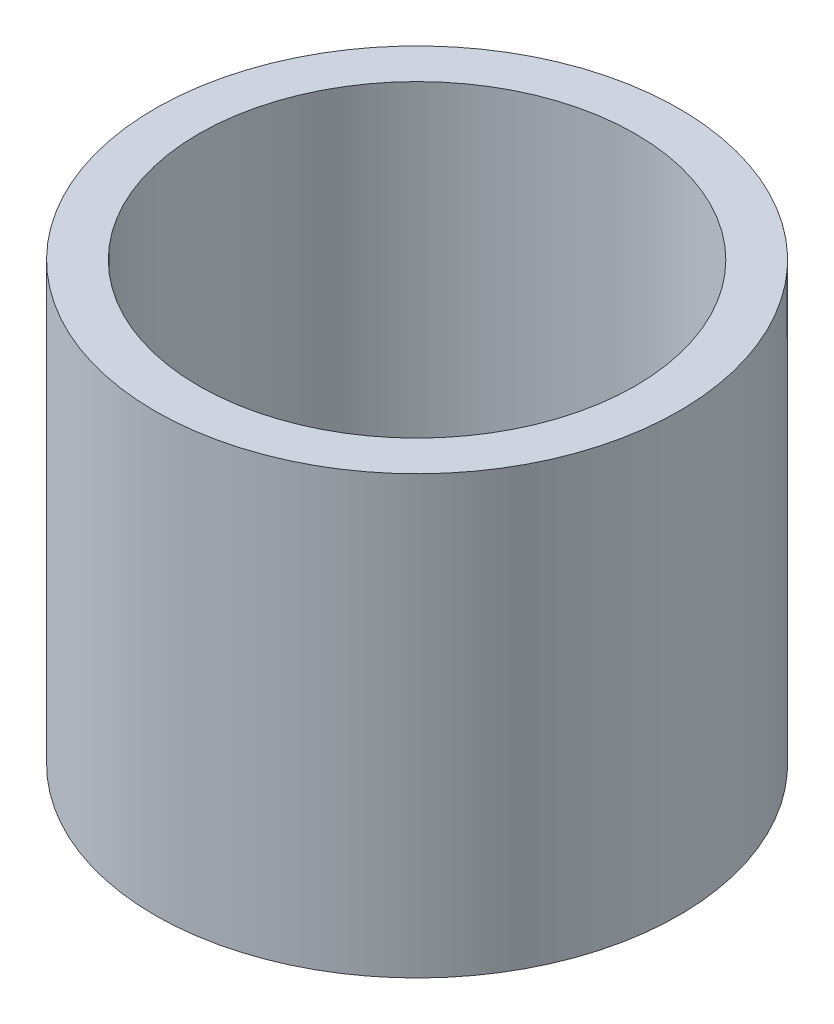
SolidWorks part; units mm, degrees
ref_plane "Front Plane" through (0, 0, 0) normal (0, 0, 1) x (1, 0, 0)
ref_plane "Top Plane" through (0, 0, 0) normal (0, 1, 0) x (1, 0, 0)
ref_plane "Right Plane" through (0, 0, 0) normal (1, 0, 0) x (0, 0, -1)
sketch "Sketch1" plane through (0, 0, 0) normal (0, 0, 1) x (1, 0, 0)
  line L0 (0, 12.4513) -> (0, -2.7566) construction
  line L1 (-2.5, 0) -> (-2.5, 5)
  line L2 (-3, 0) -> (-3, 5)
  line L3 (-3, 5) -> (-2.5, 5)
  line L4 (-3, 0) -> (-2.5, 0)
  dimension "D1" = 5
  dimension "D2" = 5
  dimension "D3" = 6
revolve "Revolve1" add sketch "Sketch1" angle 360 about L0
equation "\"D2@Sketch1\"= 4.2 + \"Hole Tolerance\""
equation "\"5mm spacing\"= 5mm"
equation "\"10mm spacing\"= 10mm"
equation "\"D1@Sketch1\" = \"5mm spacing\""
equation "\"Hole Tolerance\"= 0.8mm"
